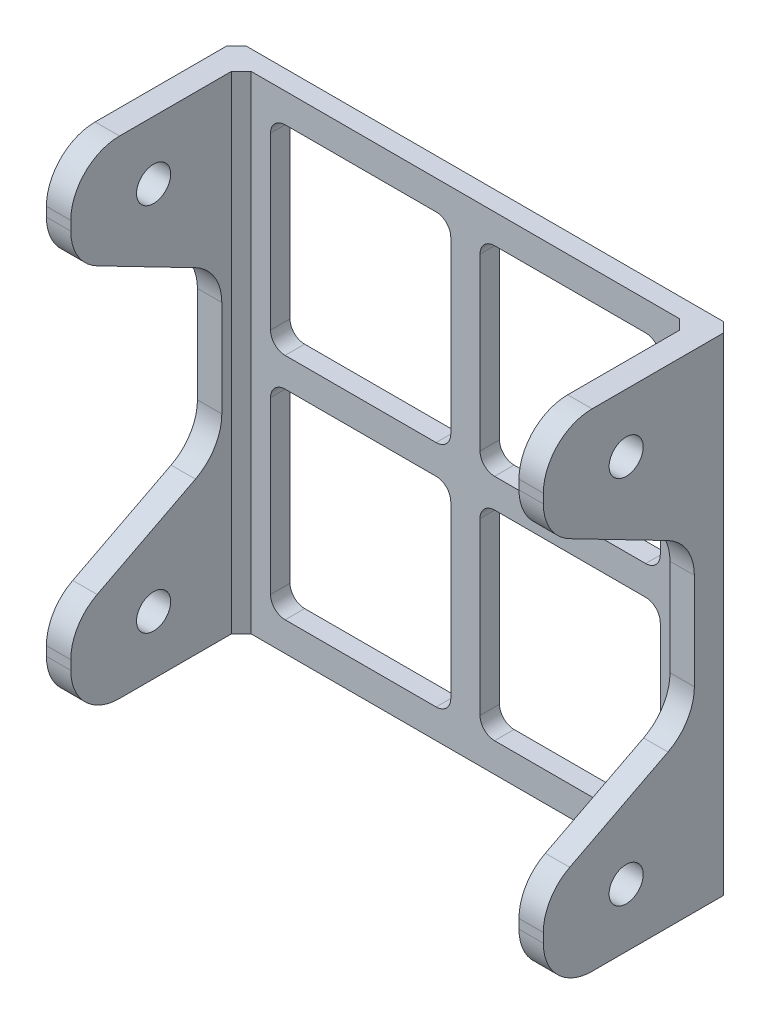
SolidWorks part; units mm, degrees
ref_plane "Plan de face" through (0, 0, 0) normal (0, 0, 1) x (1, 0, 0)
ref_plane "Plan de dessus" through (0, 0, 0) normal (0, 1, 0) x (1, 0, 0)
ref_plane "Plan de droite" through (0, 0, 0) normal (1, 0, 0) x (0, 0, -1)
sketch "Esquisse1" plane through (0, 0, 0) normal (0, 0, 1) x (1, 0, 0)
  line L1 (0, 0) -> (102, 0)
  line L2 (0, 0) -> (0, 100)
  line L3 (0, 100) -> (102, 100)
  line L4 (102, 0) -> (102, 100)
  dimension "D1" = 102
  dimension "D2" = 100
extrude "Boss.-Extru.1" add sketch "Esquisse1" along normal blind 4
sketch "Esquisse2" plane through (0, 0, 4) normal (0, 0, 1) x (1, 0, 0)
  line L0 (51, 0) -> (51, 100) construction
  line L1 (0, 0) -> (102, 0) construction
  line L2 (102, 100) -> (0, 100) construction
  line L3 (5, 0) -> (5, 100)
  line L4 (102, 0) -> (97, 0)
  line L5 (102, 0) -> (102, 100)
  line L6 (102, 100) -> (97, 100)
  line L7 (97, 0) -> (97, 100)
  line L8 (0, 100) -> (5, 100)
  line L9 (0, 0) -> (0, 100)
  line L10 (0, 0) -> (5, 0)
  dimension "D1" = 5
extrude "Boss.-Extru.2" add sketch "Esquisse2" along normal blind 35
sketch "Esquisse3" plane through (0, 0, 0) normal (-1, 0, 0) x (0, 0, 1)
  line L0 (0, 12) -> (22, 12) construction
  line L1 (0, 100) -> (0, 0) construction
  line L2 (0, 50) -> (39, 50) construction
  line L3 (39, 100) -> (39, 0) construction
  circle A0 centre (22, 12) radius 3.5
  circle A1 centre (22, 88) radius 3.5
  dimension "D1" = 7
  dimension "D2" = 38
  dimension "D3" = 22
extrude "Enlèv. mat.-Extru.1" cut sketch "Esquisse3" against normal through all both and the other way through all
sketch "Esquisse4" plane through (0, 0, 0) normal (-1, 0, 0) x (0, 0, 1)
  line L0 (39, 82) -> (8, 66)
  line L1 (39, 100) -> (39, 0) construction
  line L2 (8, 66) -> (8, 34)
  line L3 (39, 50) -> (8, 50) construction
  line L4 (39, 100) -> (0, 100) construction
  line L5 (0, 100) -> (0, 0) construction
  line L6 (39, 18) -> (8, 34)
  line L7 (39, 18) -> (39, 82)
  dimension "D1" = 18
  dimension "D2" = 8
  dimension "D3" = 16
extrude "Enlèv. mat.-Extru.2" cut sketch "Esquisse4" against normal through all both and the other way through all
fillet "Congé1" radius 10 12 edges at (99.5, 34, 8) (99.5, 66, 8) (2.5, 66, 8) (2.5, 34, 8) (2.5, 18, 39) (2.5, 0, 39) (99.5, 0, 39) (99.5, 18, 39) (99.5, 82, 39) (99.5, 100, 39) (2.5, 100, 39) (2.5, 82, 39)
sketch "Esquisse5" plane through (0, 0, 4) normal (0, 0, 1) x (1, 0, 0)
  line L0 (51, 100) -> (51, 0) construction
  line L1 (97, 100) -> (5, 100) construction
  line L2 (5, 0) -> (97, 0) construction
  line L3 (5, 50) -> (51, 50) construction
  line L4 (5, 59.9079) -> (5, 40.0921) construction
  line L5 (5, 0) -> (5, 100) construction
  line L6 (11, 94) -> (48, 94)
  line L7 (11, 94) -> (11, 53)
  line L8 (11, 53) -> (48, 53)
  line L9 (48, 94) -> (48, 53)
  line L10 (48, 6) -> (48, 47)
  line L11 (11, 47) -> (48, 47)
  line L12 (11, 6) -> (11, 47)
  line L13 (11, 6) -> (48, 6)
  line L14 (91, 6) -> (54, 6)
  line L15 (91, 6) -> (91, 47)
  line L16 (91, 47) -> (54, 47)
  line L17 (54, 6) -> (54, 47)
  line L18 (54, 94) -> (54, 53)
  line L19 (91, 53) -> (54, 53)
  line L20 (91, 94) -> (91, 53)
  line L21 (91, 94) -> (54, 94)
  dimension "D1" = 6
  dimension "D2" = 6
  dimension "D3" = 6
  dimension "D4" = 6
extrude "Enlèv. mat.-Extru.3" cut sketch "Esquisse5" against normal through all both and the other way through all
fillet "Congé2" radius 3 16 edges at (91, 94, 2) (54, 94, 2) (54, 53, 2) (91, 53, 2) (91, 6, 2) (91, 47, 2) (54, 47, 2) (54, 6, 2) (11, 6, 2) (48, 6, 2) (48, 47, 2) (11, 47, 2) (11, 53, 2) (48, 53, 2) (48, 94, 2) (11, 94, 2)
chamfer "Chanfrein1" distance 2 angle 45 4 edges at (102, 50, 0) (0, 50, 0) (5, 50, 4) (97, 50, 4)
